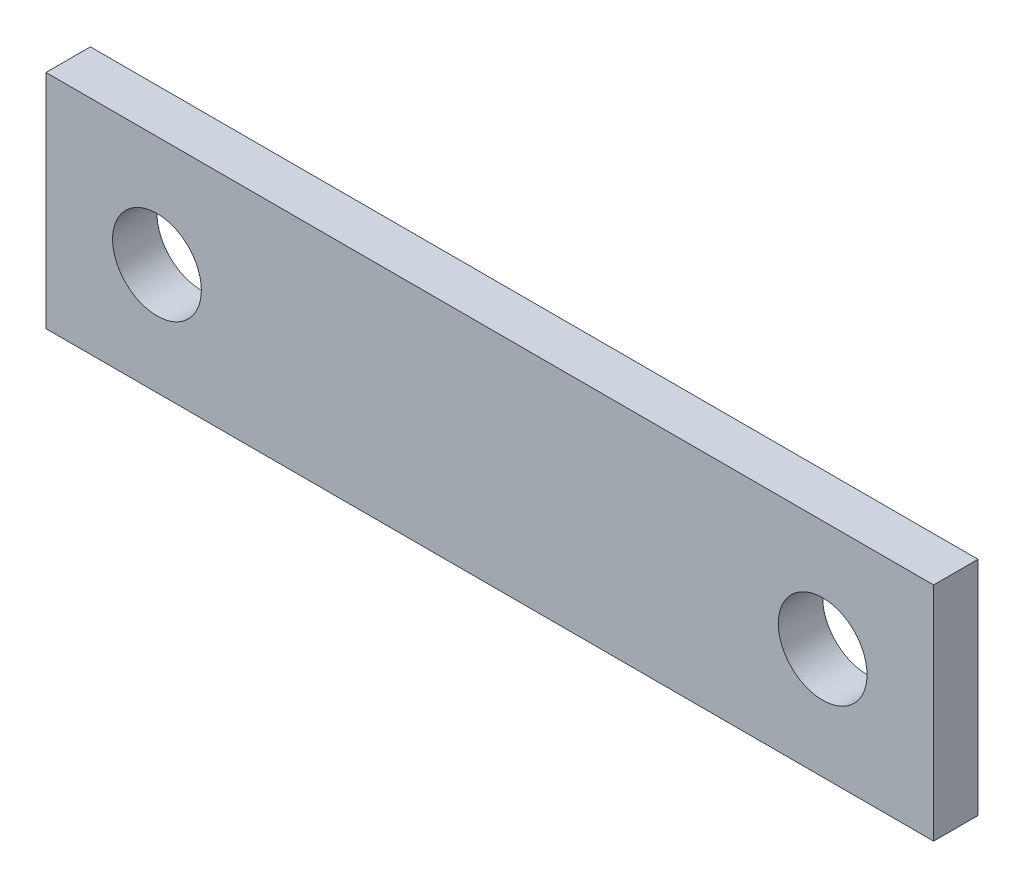
SolidWorks part; units mm, degrees
ref_plane "前视基准面" through (0, 0, 0) normal (0, 0, 1) x (1, 0, 0)
ref_plane "上视基准面" through (0, 0, 0) normal (0, 1, 0) x (1, 0, 0)
ref_plane "右视基准面" through (0, 0, 0) normal (1, 0, 0) x (0, 0, -1)
sketch "草图1" plane through (0, 0, 0) normal (0, 0, 1) x (1, 0, 0)
  line L0 (-1000, 15) -> (49000, 15) construction
  line L1 (0, 0) -> (120, 0)
  line L2 (0, 0) -> (0, 30)
  line L3 (0, 30) -> (120, 30)
  line L4 (120, 0) -> (120, 30)
  line L5 (60, -970) -> (60, 49030) construction
  circle A0 centre (15, 15) radius 6
  circle A1 centre (105, 15) radius 6
  point P8 (0, 15)
  point P11 (60, 30)
  dimension "D4" = 12
  dimension "D5" = 12
  dimension "D1" = 120
  dimension "D2" = 30
  dimension "D3" = 90
extrude "凸台-拉伸1" add sketch "草图1" along normal blind 6
